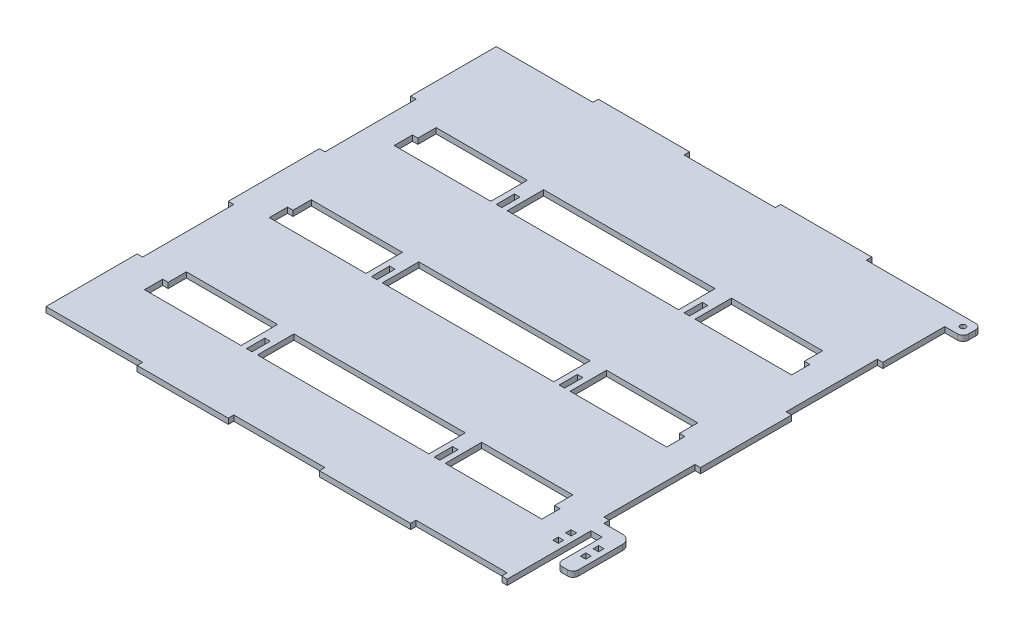
SolidWorks part; units mm, degrees
ref_plane "Front Plane" through (0, 0, 0) normal (0, 0, 1) x (1, 0, 0)
ref_plane "Top Plane" through (0, 0, 0) normal (0, 1, 0) x (1, 0, 0)
ref_plane "Right Plane" through (0, 0, 0) normal (1, 0, 0) x (0, 0, -1)
sketch "Sketch1" plane through (0, 0, 0) normal (0, 1, 0) x (1, 0, 0)
  line L0 (256, 103) -> (256, 153)
  line L1 (0, 0) -> (53, 0)
  line L2 (0, 0) -> (0, 50)
  line L3 (53, 250) -> (103, 250)
  line L4 (256, 0) -> (256, 43)
  line L5 (0, 200) -> (0, 247)
  line L6 (153, 250) -> (203, 250)
  line L7 (256, 50) -> (266.1, 50)
  line L8 (256, 0) -> (256, -3)
  line L9 (256, 203) -> (253, 203)
  line L10 (256, -3) -> (253, -3)
  line L11 (256, 153) -> (253, 153)
  line L12 (253, 203) -> (253, 153)
  line L13 (203, 0) -> (253, 0)
  line L14 (153, 0) -> (153, -3)
  line L15 (153, -3) -> (203, -3)
  line L16 (203, 0) -> (203, -3)
  line L17 (0, 200) -> (3, 200)
  line L18 (0, 100) -> (0, 150)
  line L19 (0, 150) -> (3, 150)
  line L20 (3, 200) -> (3, 150)
  line L21 (253, 0) -> (253, -3)
  line L22 (103, 0) -> (103, -3)
  line L23 (103, -3) -> (53, -3)
  line L24 (53, 0) -> (53, -3)
  line L25 (265.1, 28) -> (268.1, 28)
  line L26 (256, 43) -> (262.1, 43)
  line L27 (271.1, 45) -> (271.1, 43)
  line L28 (265.1, 28) -> (265.1, 31)
  line L29 (256, 103) -> (253, 103)
  line L30 (256, 203) -> (256, 237)
  line L31 (81, 35) -> (175, 35)
  line L32 (253, 103) -> (253, 53)
  line L33 (0, 100) -> (3, 100)
  line L34 (103, 0) -> (153, 0)
  line L35 (0, 50) -> (3, 50)
  line L36 (3, 100) -> (3, 50)
  line L37 (253, 247) -> (263, 247)
  line L38 (271.1, 43) -> (271.1, 21)
  line L39 (256, 237) -> (263, 237)
  line L40 (266, 244) -> (266, 240)
  line L41 (268.1, 18) -> (265.1, 18)
  line L42 (262.1, 43) -> (262.1, 21)
  line L43 (265.1, 31) -> (268.1, 31)
  line L44 (268.1, 28) -> (268.1, 31)
  line L45 (265.1, 35) -> (268.1, 35)
  line L46 (265.1, 35) -> (265.1, 38)
  line L47 (265.1, 38) -> (268.1, 38)
  line L48 (268.1, 35) -> (268.1, 38)
  line L49 (250, 28) -> (253, 28)
  line L50 (250, 28) -> (250, 31)
  line L51 (250, 31) -> (253, 31)
  line L52 (253, 28) -> (253, 31)
  line L53 (250, 35) -> (253, 35)
  line L54 (250, 35) -> (250, 38)
  line L55 (250, 38) -> (253, 38)
  line L56 (253, 35) -> (253, 38)
  line L57 (184, 35) -> (234, 35)
  line L58 (75, 35) -> (75, 45)
  line L59 (0, 247) -> (53, 247)
  line L60 (53, 250) -> (53, 247)
  line L61 (103, 247) -> (153, 247)
  line L62 (103, 247) -> (103, 250)
  line L63 (75, 45) -> (78, 45)
  line L64 (153, 247) -> (153, 250)
  line L65 (253, 53) -> (256, 53)
  line L66 (78, 35) -> (78, 45)
  line L67 (253, 247) -> (203, 247)
  line L68 (203, 250) -> (203, 247)
  line L69 (256, 50) -> (256, 53)
  line L70 (184, 103.5) -> (234, 103.5)
  line L71 (178, 35) -> (178, 45)
  line L72 (178, 45) -> (181, 45)
  line L73 (181, 35) -> (181, 45)
  line L74 (81, 103.5) -> (175, 103.5)
  line L75 (75, 103.5) -> (75, 113.5)
  line L76 (75, 113.5) -> (78, 113.5)
  line L77 (78, 103.5) -> (78, 113.5)
  line L78 (81, 172) -> (175, 172)
  line L79 (178, 103.5) -> (178, 113.5)
  line L80 (178, 113.5) -> (181, 113.5)
  line L81 (181, 103.5) -> (181, 113.5)
  line L82 (184, 172) -> (234, 172)
  line L83 (75, 172) -> (75, 182)
  line L84 (75, 182) -> (78, 182)
  line L85 (78, 172) -> (78, 182)
  line L86 (81, 55) -> (175, 55)
  line L87 (178, 172) -> (178, 182)
  line L88 (178, 182) -> (181, 182)
  line L89 (181, 172) -> (181, 182)
  line L90 (22, 35) -> (72, 35)
  line L91 (22, 45) -> (22, 55)
  line L92 (22, 55) -> (72, 55)
  line L93 (234, 45) -> (234, 55)
  line L94 (22, 103.5) -> (72, 103.5)
  line L95 (22, 113.5) -> (22, 123.5)
  line L96 (22, 123.5) -> (72, 123.5)
  line L97 (234, 123.5) -> (234, 113.5)
  line L98 (22, 172) -> (72, 172)
  line L99 (22, 182) -> (22, 192)
  line L100 (22, 192) -> (72, 192)
  line L101 (234, 182) -> (234, 192)
  line L102 (184, 55) -> (234, 55)
  line L103 (72, 35) -> (72, 55)
  line L104 (184, 123.5) -> (234, 123.5)
  line L105 (81, 35) -> (81, 55)
  line L106 (178, 35) -> (181, 35)
  line L107 (175, 35) -> (175, 55)
  line L108 (81, 123.5) -> (175, 123.5)
  line L109 (184, 35) -> (184, 55)
  line L110 (178, 103.5) -> (181, 103.5)
  line L111 (175, 103.5) -> (175, 123.5)
  line L112 (81, 192) -> (175, 192)
  line L113 (184, 103.5) -> (184, 123.5)
  line L114 (75, 103.5) -> (78, 103.5)
  line L115 (72, 103.5) -> (72, 123.5)
  line L116 (184, 192) -> (234, 192)
  line L117 (81, 103.5) -> (81, 123.5)
  line L118 (75, 172) -> (78, 172)
  line L119 (72, 172) -> (72, 192)
  line L120 (234, 103.5) -> (237, 103.5)
  line L121 (81, 172) -> (81, 192)
  line L122 (178, 172) -> (181, 172)
  line L123 (175, 172) -> (175, 192)
  line L124 (234, 172) -> (237, 172)
  line L125 (184, 172) -> (184, 192)
  line L126 (75, 35) -> (78, 35)
  line L127 (22, 103.5) -> (19, 103.5)
  line L128 (234, 182) -> (237, 182)
  line L129 (237, 172) -> (237, 182)
  line L130 (22, 172) -> (19, 172)
  line L132 (22, 182) -> (19, 182)
  line L133 (19, 172) -> (19, 182)
  line L134 (22, 113.5) -> (19, 113.5)
  line L135 (19, 103.5) -> (19, 113.5)
  line L136 (234, 113.5) -> (237, 113.5)
  line L137 (237, 103.5) -> (237, 113.5)
  line L140 (234, 35) -> (237, 35)
  line L142 (234, 45) -> (237, 45)
  line L143 (237, 35) -> (237, 45)
  line L144 (22, 35) -> (19, 35)
  line L146 (22, 45) -> (19, 45)
  line L147 (19, 35) -> (19, 45)
  circle A0 centre (261, 242) radius 1.5
  arc A1 (263, 247) -> (266, 244) centre (263, 244) cw
  arc A2 (263, 237) -> (266, 240) centre (263, 240) ccw
  arc A3 (266.1, 50) -> (271.1, 45) centre (266.1, 45) cw
  arc A4 (265.1, 18) -> (262.1, 21) centre (265.1, 21) cw
  arc A5 (271.1, 21) -> (268.1, 18) centre (268.1, 21) cw
  point P44 (266, 247)
  point P47 (266, 237)
  point P65 (251.5, 31)
  point P68 (271.1, 50)
  point P71 (262.1, 18)
  point P74 (271.1, 18)
  point P144 (178, 177)
  dimension "D7" = 3
  dimension "D8" = 5
  dimension "D9" = 5
  dimension "D10" = 3
  dimension "D45" = 5
  dimension "D46" = 3
  dimension "D1" = 256
  dimension "D3" = 50
  dimension "D4" = 3
  dimension "D5" = 10
  dimension "D6" = 10
  dimension "D11" = 47
  dimension "D12" = 34
  dimension "D13" = 10
  dimension "D14" = 10.1
  dimension "D15" = 3
  dimension "D16" = 3
  dimension "D17" = 50
  dimension "D18" = 53
  dimension "D19" = 50
  dimension "D20" = 50
  dimension "D21" = 50
  dimension "D22" = 50
  dimension "D23" = 50
  dimension "D24" = 5
  dimension "D25" = 44
  dimension "D26" = 3
  dimension "D27" = 3
  dimension "D28" = 3
  dimension "D29" = 50
  dimension "D30" = 7
  dimension "D31" = 25
  dimension "D32" = 9
  dimension "D33" = 6.1
  dimension "D34" = 43
  dimension "D35" = 25
  dimension "D36" = 4
  dimension "D37" = 4
  dimension "D38" = 10
  dimension "D39" = 3
  dimension "D40" = 10
  dimension "D41" = 3
  dimension "D42" = 3
  dimension "D43" = 3
  dimension "D44" = 3
  dimension "D47" = 53
  dimension "D48" = 50
  dimension "D49" = 50
  dimension "D50" = 50
  dimension "D51" = 247
  dimension "D52" = 3
  dimension "D53" = 50
  dimension "D54" = 3
  dimension "D55" = 3
  dimension "D56" = 50
  dimension "D57" = 10
  dimension "D58" = 58.5
  dimension "D59" = 58.5
  dimension "D60" = 58.5
  dimension "D61" = 58.5
  dimension "D62" = 65
  dimension "D63" = 65
  dimension "D64" = 100
  dimension "D65" = 75
  dimension "D66" = 3
  dimension "D67" = 10
  dimension "D68" = 3
  dimension "D69" = 3
  dimension "D70" = 20
  dimension "D71" = 20
  dimension "D72" = 3
  dimension "D73" = 3
  dimension "D74" = 10
  dimension "D75" = 3
  dimension "D76" = 20
  dimension "D77" = 3
  dimension "D78" = 20
  dimension "D79" = 20
  dimension "D80" = 3
  dimension "D81" = 3
  dimension "D82" = 3
  dimension "D83" = 10
  dimension "D84" = 20
  dimension "D85" = 10
  dimension "D86" = 10
  dimension "D87" = 3
  dimension "D88" = 3
  dimension "D89" = 3
  dimension "D90" = 3
  dimension "D91" = 20
  dimension "D92" = 20
  dimension "D93" = 20
  dimension "D94" = 20
  dimension "D95" = 50
  dimension "D96" = 50
  dimension "D97" = 50
  dimension "D98" = 50
  dimension "D99" = 50
  dimension "D100" = 50
  dimension "D101" = 20
  dimension "D102" = 20
  dimension "D103" = 20
  dimension "D104" = 20
  dimension "D105" = 20
  dimension "D106" = 10
  dimension "D107" = 10
  dimension "D108" = 10
  dimension "D109" = 3
  dimension "D110" = 50
  dimension "D111" = 50
  dimension "D112" = 3
extrude "Boss-Extrude1" add sketch "Sketch1" along normal blind 3
equation "\"w\"=3"
equation "\"L\"=50"
